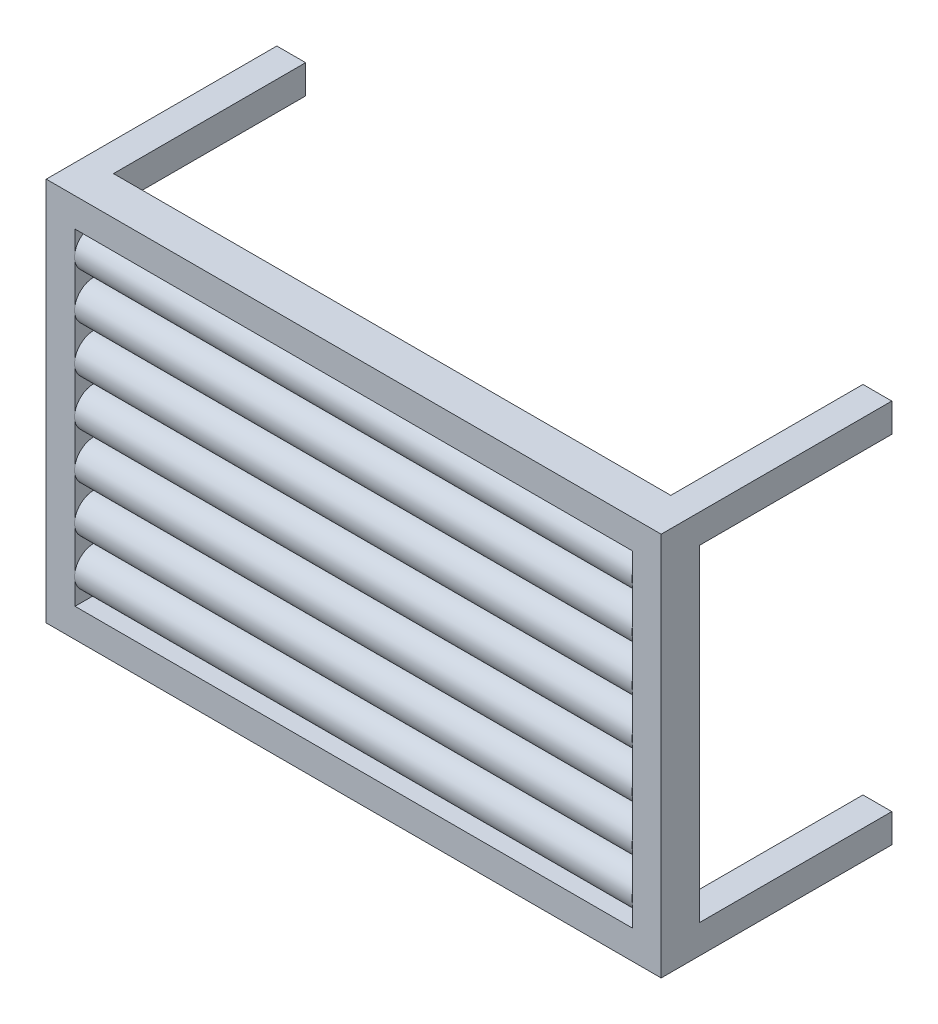
SolidWorks part; units mm, degrees
ref_plane "Front Plane" through (0, 0, 0) normal (0, 0, 1) x (1, 0, 0)
ref_plane "Top Plane" through (0, 0, 0) normal (0, 1, 0) x (1, 0, 0)
ref_plane "Right Plane" through (0, 0, 0) normal (1, 0, 0) x (0, 0, -1)
sketch "Sketch1" plane through (0, 0, 0) normal (0, 0, 1) x (1, 0, 0)
  line L0 (19.05, 234.95) -> (387.35, 234.95)
  line L1 (0, 0) -> (406.4, 0)
  line L2 (0, 0) -> (0, 254)
  line L3 (0, 254) -> (406.4, 254)
  line L4 (406.4, 0) -> (406.4, 254)
  line L5 (387.35, 19.05) -> (387.35, 234.95)
  line L6 (19.05, 19.05) -> (387.35, 19.05)
  line L7 (19.05, 19.05) -> (19.05, 234.95)
  dimension "D1" = 406.4
  dimension "D2" = 254
  dimension "D3" = 19.05
extrude "Boss-Extrude1" add sketch "Sketch1" along normal blind 25.4
sketch "Sketch2" plane through (19.05, 0, 0) normal (1, 0, 0) x (0, 0, -1)
  circle A0 centre (-13.0016, 219.0467) radius 12.7
  circle A1 centre (-13.0016, 188.5667) radius 12.7
  circle A2 centre (-13.0016, 158.0867) radius 12.7
  circle A3 centre (-13.0016, 127.6067) radius 12.7
  circle A4 centre (-13.0016, 97.1267) radius 12.7
  circle A5 centre (-13.0016, 66.6467) radius 12.7
  circle A6 centre (-13.0016, 36.1667) radius 12.7
  point P0 (-13.0016, 219.0467)
  point P16 (-12.89, 221.0657)
  dimension "D2" = 25.4
  dimension "D3" = 38.4327
  dimension "D4" = 36.1667
  dimension "D1" = 7
extrude "Boss-Extrude2" add sketch "Sketch2" along direction (-1, 0, 0) on the side of the normal up to surface (368.3 mm away)
sketch "Sketch3" plane through (0, 0, 0) normal (0, 0, -1) x (-1, 0, 0)
  line L0 (-406.4, 254) -> (0, 254) construction
  line L1 (-387.35, 234.95) -> (-406.4, 234.95)
  line L2 (-387.35, 234.95) -> (-387.35, 254)
  line L3 (-387.35, 254) -> (-406.4, 254)
  line L4 (-406.4, 234.95) -> (-406.4, 254)
  line L5 (-406.4, 0) -> (-406.4, 254) construction
  line L6 (0, 254) -> (0, 0) construction
  line L7 (-387.35, 19.05) -> (-406.4, 19.05)
  line L8 (-387.35, 19.05) -> (-387.35, 0)
  line L9 (-387.35, 0) -> (-406.4, 0)
  line L10 (-406.4, 19.05) -> (-406.4, 0)
  line L11 (-19.05, 234.95) -> (0, 234.95)
  line L12 (-19.05, 234.95) -> (-19.05, 254)
  line L13 (-19.05, 254) -> (0, 254)
  line L14 (0, 234.95) -> (0, 254)
  line L16 (-19.05, 19.05) -> (0, 19.05)
  line L17 (-19.05, 19.05) -> (-19.05, 0)
  line L18 (-19.05, 0) -> (0, 0)
  line L19 (0, 19.05) -> (0, 0)
extrude "Boss-Extrude3" add sketch "Sketch3" along normal blind 127
